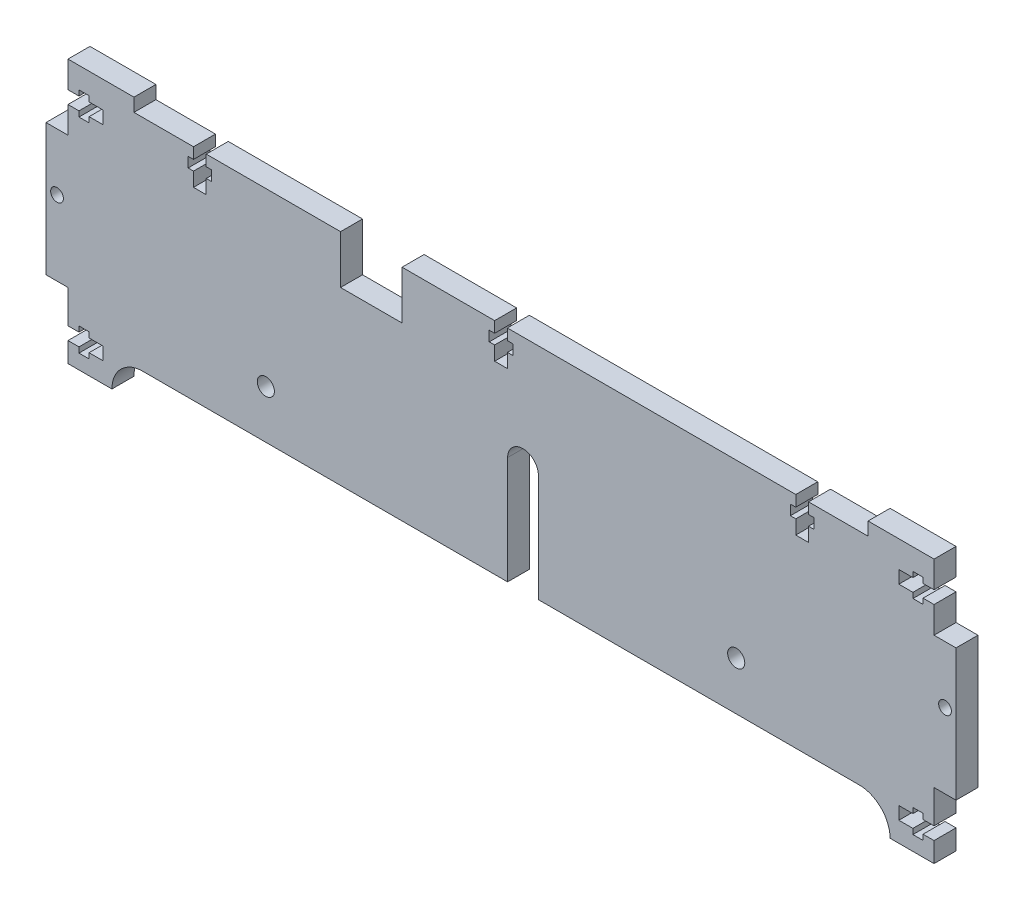
SolidWorks part; units mm, degrees
ref_plane "Front Plane" through (0, 0, 0) normal (0, 0, 1) x (1, 0, 0)
ref_plane "Top Plane" through (0, 0, 0) normal (0, 1, 0) x (1, 0, 0)
ref_plane "Right Plane" through (0, 0, 0) normal (1, 0, 0) x (0, 0, -1)
sketch "Sketch1" plane through (0, 0, 0) normal (0, 0, 1) x (1, 0, 0)
  line L18 (-83.5, 48) -> (-83.5, 51)
  line L19 (-83.5, 51) -> (-98.5, 51)
  line L20 (-98.5, 51) -> (-98.5, 44.95)
  line L21 (-98.5, 36) -> (-103.5, 36)
  line L22 (-103.5, 36) -> (-103.5, 6)
  line L23 (-103.5, 6) -> (-98.5, 6)
  line L24 (-98.5, 6) -> (-98.5, -1.55)
  line L25 (-98.5, -9) -> (-88.5, -9)
  line L26 (-81.5, -2) -> (81.5, -2)
  line L27 (88.5, -9) -> (98.5, -9)
  line L28 (98.5, -9) -> (98.5, -4.45)
  line L29 (98.5, 6) -> (103.5, 6)
  line L30 (103.5, 6) -> (103.5, 36)
  line L31 (103.5, 36) -> (98.5, 36)
  line L32 (98.5, 36) -> (98.5, 42.05)
  line L33 (98.5, 51) -> (83.5, 51)
  line L34 (83.5, 51) -> (83.5, 48)
  line L35 (83.5, 48) -> (69.95, 48)
  line L36 (-83.5, 48) -> (-83.5, 51)
  line L37 (-83.5, 51) -> (-98.5, 51)
  line L38 (-98.5, 51) -> (-98.5, 44.95)
  line L39 (-98.5, 36) -> (-103.5, 36)
  line L40 (-103.5, 36) -> (-103.5, 6)
  line L41 (-103.5, 6) -> (-98.5, 6)
  line L42 (-98.5, 6) -> (-98.5, -1.55)
  line L43 (-98.5, -9) -> (-88.5, -9)
  line L44 (-81.5, -2) -> (81.5, -2)
  line L45 (88.5, -9) -> (98.5, -9)
  line L46 (98.5, -9) -> (98.5, -4.45)
  line L47 (98.5, 6) -> (103.5, 6)
  line L48 (103.5, 6) -> (103.5, 36)
  line L49 (103.5, 36) -> (98.5, 36)
  line L50 (98.5, 36) -> (98.5, 42.05)
  line L51 (98.5, 51) -> (83.5, 51)
  line L52 (83.5, 51) -> (83.5, 48)
  line L53 (83.5, 48) -> (69.95, 48)
  line L280 (96, 46.175) -> (96, 44.95)
  line L281 (96, 46.175) -> (96, 44.95)
  line L282 (96, 44.95) -> (98.5, 44.95)
  line L283 (96, 44.95) -> (98.5, 44.95)
  line L284 (98.5, 44.95) -> (98.5, 51)
  line L285 (98.5, 44.95) -> (98.5, 51)
  line L286 (69.95, 48) -> (69.95, 45.5)
  line L287 (69.95, 48) -> (69.95, 45.5)
  line L288 (69.95, 45.5) -> (71.175, 45.5)
  line L289 (69.95, 45.5) -> (71.175, 45.5)
  line L290 (71.175, 45.5) -> (71.175, 43.2)
  line L291 (71.175, 45.5) -> (71.175, 43.2)
  line L292 (71.175, 43.2) -> (69.95, 43.2)
  line L293 (71.175, 43.2) -> (69.95, 43.2)
  line L294 (69.95, 43.2) -> (69.95, 40)
  line L295 (69.95, 43.2) -> (69.95, 40)
  line L296 (69.95, 40) -> (67.05, 40)
  line L297 (69.95, 40) -> (67.05, 40)
  line L298 (67.05, 40) -> (67.05, 43.2)
  line L299 (67.05, 40) -> (67.05, 43.2)
  line L300 (67.05, 43.2) -> (65.825, 43.2)
  line L301 (67.05, 43.2) -> (65.825, 43.2)
  line L302 (65.825, 43.2) -> (65.825, 45.5)
  line L303 (65.825, 43.2) -> (65.825, 45.5)
  line L304 (65.825, 45.5) -> (67.05, 45.5)
  line L305 (65.825, 45.5) -> (67.05, 45.5)
  line L306 (67.05, 45.5) -> (67.05, 48)
  line L307 (67.05, 45.5) -> (67.05, 48)
  line L308 (67.05, 48) -> (1.45, 48)
  line L309 (67.05, 48) -> (1.45, 48)
  line L310 (1.45, 48) -> (1.45, 45.5)
  line L311 (1.45, 48) -> (1.45, 45.5)
  line L312 (1.45, 45.5) -> (2.675, 45.5)
  line L313 (1.45, 45.5) -> (2.675, 45.5)
  line L314 (2.675, 45.5) -> (2.675, 43.2)
  line L315 (2.675, 45.5) -> (2.675, 43.2)
  line L316 (2.675, 43.2) -> (1.45, 43.2)
  line L317 (2.675, 43.2) -> (1.45, 43.2)
  line L318 (1.45, 43.2) -> (1.45, 40)
  line L319 (1.45, 43.2) -> (1.45, 40)
  line L320 (1.45, 40) -> (-1.45, 40)
  line L321 (1.45, 40) -> (-1.45, 40)
  line L322 (-1.45, 40) -> (-1.45, 43.2)
  line L323 (-1.45, 40) -> (-1.45, 43.2)
  line L324 (-1.45, 43.2) -> (-2.675, 43.2)
  line L325 (-1.45, 43.2) -> (-2.675, 43.2)
  line L326 (-2.675, 43.2) -> (-2.675, 45.5)
  line L327 (-2.675, 43.2) -> (-2.675, 45.5)
  line L328 (-2.675, 45.5) -> (-1.45, 45.5)
  line L329 (-2.675, 45.5) -> (-1.45, 45.5)
  line L330 (-1.45, 45.5) -> (-1.45, 48)
  line L331 (-1.45, 45.5) -> (-1.45, 48)
  line L332 (-1.45, 48) -> (-67.05, 48)
  line L333 (-1.45, 48) -> (-67.05, 48)
  line L334 (-67.05, 48) -> (-67.05, 45.5)
  line L335 (-67.05, 48) -> (-67.05, 45.5)
  line L336 (-67.05, 45.5) -> (-65.825, 45.5)
  line L337 (-67.05, 45.5) -> (-65.825, 45.5)
  line L338 (-65.825, 45.5) -> (-65.825, 43.2)
  line L339 (-65.825, 45.5) -> (-65.825, 43.2)
  line L340 (-65.825, 43.2) -> (-67.05, 43.2)
  line L341 (-65.825, 43.2) -> (-67.05, 43.2)
  line L342 (-67.05, 43.2) -> (-67.05, 40)
  line L343 (-67.05, 43.2) -> (-67.05, 40)
  line L344 (-67.05, 40) -> (-69.95, 40)
  line L345 (-67.05, 40) -> (-69.95, 40)
  line L346 (-69.95, 40) -> (-69.95, 43.2)
  line L347 (-69.95, 40) -> (-69.95, 43.2)
  line L348 (-69.95, 43.2) -> (-71.175, 43.2)
  line L349 (-69.95, 43.2) -> (-71.175, 43.2)
  line L350 (-71.175, 43.2) -> (-71.175, 45.5)
  line L351 (-71.175, 43.2) -> (-71.175, 45.5)
  line L352 (-71.175, 45.5) -> (-69.95, 45.5)
  line L353 (-71.175, 45.5) -> (-69.95, 45.5)
  line L354 (-69.95, 45.5) -> (-69.95, 48)
  line L355 (-69.95, 45.5) -> (-69.95, 48)
  line L356 (-69.95, 48) -> (-83.5, 48)
  line L357 (-69.95, 48) -> (-83.5, 48)
  line L358 (-98.5, 44.95) -> (-96, 44.95)
  line L359 (-98.5, 44.95) -> (-96, 44.95)
  line L360 (-96, 44.95) -> (-96, 46.175)
  line L361 (-96, 44.95) -> (-96, 46.175)
  line L362 (-96, 46.175) -> (-93.7, 46.175)
  line L363 (-96, 46.175) -> (-93.7, 46.175)
  line L364 (-93.7, 46.175) -> (-93.7, 44.95)
  line L365 (-93.7, 46.175) -> (-93.7, 44.95)
  line L366 (-93.7, 44.95) -> (-90.5, 44.95)
  line L367 (-93.7, 44.95) -> (-90.5, 44.95)
  line L368 (-90.5, 44.95) -> (-90.5, 42.05)
  line L369 (-90.5, 44.95) -> (-90.5, 42.05)
  line L370 (-90.5, 42.05) -> (-93.7, 42.05)
  line L371 (-90.5, 42.05) -> (-93.7, 42.05)
  line L372 (-93.7, 42.05) -> (-93.7, 40.825)
  line L373 (-93.7, 42.05) -> (-93.7, 40.825)
  line L374 (-93.7, 40.825) -> (-96, 40.825)
  line L375 (-93.7, 40.825) -> (-96, 40.825)
  line L376 (-96, 40.825) -> (-96, 42.05)
  line L377 (-96, 40.825) -> (-96, 42.05)
  line L378 (-96, 42.05) -> (-98.5, 42.05)
  line L379 (-96, 42.05) -> (-98.5, 42.05)
  line L380 (-98.5, 42.05) -> (-98.5, 36)
  line L381 (-98.5, 42.05) -> (-98.5, 36)
  line L382 (-98.5, -1.55) -> (-96, -1.55)
  line L383 (-98.5, -1.55) -> (-96, -1.55)
  line L384 (-96, -1.55) -> (-96, -0.325)
  line L385 (-96, -1.55) -> (-96, -0.325)
  line L386 (-96, -0.325) -> (-93.7, -0.325)
  line L387 (-96, -0.325) -> (-93.7, -0.325)
  line L388 (-93.7, -0.325) -> (-93.7, -1.55)
  line L389 (-93.7, -0.325) -> (-93.7, -1.55)
  line L390 (-93.7, -1.55) -> (-90.5, -1.55)
  line L391 (-93.7, -1.55) -> (-90.5, -1.55)
  line L392 (-90.5, -1.55) -> (-90.5, -4.45)
  line L393 (-90.5, -1.55) -> (-90.5, -4.45)
  line L394 (-90.5, -4.45) -> (-93.7, -4.45)
  line L395 (-90.5, -4.45) -> (-93.7, -4.45)
  line L396 (-93.7, -4.45) -> (-93.7, -5.675)
  line L397 (-93.7, -4.45) -> (-93.7, -5.675)
  line L398 (-93.7, -5.675) -> (-96, -5.675)
  line L399 (-93.7, -5.675) -> (-96, -5.675)
  line L400 (-96, -5.675) -> (-96, -4.45)
  line L401 (-96, -5.675) -> (-96, -4.45)
  line L402 (-96, -4.45) -> (-98.5, -4.45)
  line L403 (-96, -4.45) -> (-98.5, -4.45)
  line L404 (-98.5, -4.45) -> (-98.5, -9)
  line L405 (-98.5, -4.45) -> (-98.5, -9)
  line L406 (98.5, -4.45) -> (96, -4.45)
  line L407 (98.5, -4.45) -> (96, -4.45)
  line L408 (96, -4.45) -> (96, -5.675)
  line L409 (96, -4.45) -> (96, -5.675)
  line L410 (96, -5.675) -> (93.7, -5.675)
  line L411 (96, -5.675) -> (93.7, -5.675)
  line L412 (93.7, -5.675) -> (93.7, -4.45)
  line L413 (93.7, -5.675) -> (93.7, -4.45)
  line L414 (93.7, -4.45) -> (90.5, -4.45)
  line L415 (93.7, -4.45) -> (90.5, -4.45)
  line L416 (90.5, -4.45) -> (90.5, -1.55)
  line L417 (90.5, -4.45) -> (90.5, -1.55)
  line L418 (90.5, -1.55) -> (93.7, -1.55)
  line L419 (90.5, -1.55) -> (93.7, -1.55)
  line L420 (93.7, -1.55) -> (93.7, -0.325)
  line L421 (93.7, -1.55) -> (93.7, -0.325)
  line L422 (93.7, -0.325) -> (96, -0.325)
  line L423 (93.7, -0.325) -> (96, -0.325)
  line L424 (96, -0.325) -> (96, -1.55)
  line L425 (96, -0.325) -> (96, -1.55)
  line L426 (96, -1.55) -> (98.5, -1.55)
  line L427 (96, -1.55) -> (98.5, -1.55)
  line L428 (98.5, -1.55) -> (98.5, 6)
  line L429 (98.5, -1.55) -> (98.5, 6)
  line L430 (98.5, 42.05) -> (96, 42.05)
  line L431 (98.5, 42.05) -> (96, 42.05)
  line L432 (96, 42.05) -> (96, 40.825)
  line L433 (96, 42.05) -> (96, 40.825)
  line L434 (96, 40.825) -> (93.7, 40.825)
  line L435 (96, 40.825) -> (93.7, 40.825)
  line L436 (93.7, 40.825) -> (93.7, 42.05)
  line L437 (93.7, 40.825) -> (93.7, 42.05)
  line L438 (93.7, 42.05) -> (90.5, 42.05)
  line L439 (93.7, 42.05) -> (90.5, 42.05)
  line L440 (90.5, 42.05) -> (90.5, 44.95)
  line L441 (90.5, 42.05) -> (90.5, 44.95)
  line L442 (90.5, 44.95) -> (93.7, 44.95)
  line L443 (90.5, 44.95) -> (93.7, 44.95)
  line L444 (93.7, 44.95) -> (93.7, 46.175)
  line L445 (93.7, 44.95) -> (93.7, 46.175)
  line L446 (93.7, 46.175) -> (96, 46.175)
  line L447 (93.7, 46.175) -> (96, 46.175)
  arc A2 (-81.5, -2) -> (-88.5, -9) centre (-81.5, -9) ccw
  arc A3 (88.5, -9) -> (81.5, -2) centre (81.5, -9) ccw
  arc A4 (-81.5, -2) -> (-88.5, -9) centre (-81.5, -9) ccw
  arc A5 (88.5, -9) -> (81.5, -2) centre (81.5, -9) ccw
  dimension "D1" = 0
extrude "Boss-Extrude1" add sketch "Sketch1" along normal blind 5
sketch "Sketch2" plane through (0, 0, 5) normal (0, 0, 1) x (1, 0, 0)
  line L0 (-103.5, 36) -> (-103.5, 6) construction
  line L1 (-36.5, 49) -> (-22.5, 49)
  line L2 (-36.5, 49) -> (-36.5, 37)
  line L3 (-36.5, 37) -> (-22.5, 37)
  line L4 (-22.5, 49) -> (-22.5, 37)
  line L5 (-98.5, -9) -> (-88.5, -9) construction
  dimension "D1" = 81
  dimension "D2" = 14
  dimension "D3" = 12
  dimension "D4" = 46
extrude "Cut-Extrude1" cut sketch "Sketch2" against normal through all
sketch "Sketch3" plane through (0, 0, 5) normal (0, 0, 1) x (1, 0, 0)
  line L0 (-103.5, 36) -> (-103.5, 6) construction
  line L1 (1.5, -2) -> (8.5, -2)
  line L2 (1.5, -2) -> (1.5, 22.5)
  line L3 (1.5, 22.5) -> (8.5, 22.5)
  line L4 (8.5, -2) -> (8.5, 22.5)
  line L6 (5, 22.5) -> (5, -2) construction
  line L9 (88.5, -9) -> (98.5, -9) construction
  line L10 (-81.5, -2) -> (81.5, -2) construction
  circle A0 centre (5, 22.5) radius 3.5
  point P4 (29.5778, -2)
  point P14 (0, 0)
  point P15 (0, 0)
  dimension "D1" = 7
  dimension "D2" = 35
  dimension "D3" = 105
extrude "Cut-Extrude2" cut sketch "Sketch3" against normal through all contours L4 L3 L2 L1 | A0
sketch "Sketch4" plane through (0, 0, 5) normal (0, 0, 1) x (1, 0, 0)
  line L0 (-67.05, 51) -> (-69.95, 51) construction
  line L1 (1.45, 51) -> (-1.45, 51) construction
  line L2 (1.45, 48) -> (1.45, 51) construction
  line L3 (-1.45, 51) -> (-1.45, 48) construction
  line L4 (-69.95, 51) -> (-69.95, 48) construction
  line L5 (-67.05, 48) -> (-67.05, 51) construction
  line L6 (-67.05, 51) -> (-69.95, 51) construction
  line L7 (1.45, 51) -> (-1.45, 51) construction
  line L8 (1.45, 48) -> (1.45, 51) construction
  line L9 (-1.45, 51) -> (-1.45, 48) construction
  line L10 (-69.95, 51) -> (-69.95, 48) construction
  line L11 (-67.05, 48) -> (-67.05, 51) construction
  line L12 (-103.5, 21.55) -> (-103.5, 24.45) construction
  line L13 (-103.5, 21.55) -> (-103.5, 24.45) construction
  line L14 (-103.5, 44.95) -> (-103.5, 42.05) construction
  line L15 (-103.5, -1.55) -> (-103.5, -4.45) construction
  line L16 (-103.5, 44.95) -> (-103.5, 42.05) construction
  line L17 (-103.5, -1.55) -> (-103.5, -4.45) construction
  line L18 (-103.5, 23) -> (-83.698, 23) construction
  line L19 (-101, 36) -> (-101, 23) construction
  line L20 (-103.5, 36) -> (-98.5, 36) construction
  line L21 (-103.5, 43.5) -> (-94.9093, 43.5) construction
  line L22 (-98.5, 51) -> (-98.5, 44.95) construction
  line L23 (-98.5, 44.95) -> (-90.5, 44.95)
  line L24 (-98.5, 44.95) -> (-98.5, 42.05)
  line L25 (-98.5, 42.05) -> (-90.5, 42.05)
  line L26 (-90.5, 44.95) -> (-90.5, 42.05)
  line L27 (-96, 46.175) -> (-93.7, 46.175)
  line L28 (-96, 46.175) -> (-96, 40.825)
  line L29 (-96, 40.825) -> (-93.7, 40.825)
  line L30 (-93.7, 46.175) -> (-93.7, 40.825)
  line L31 (-103.5, 20.325) -> (-69.95, 20.325) construction
  line L32 (-98.5, -9) -> (-98.5, 6) construction
  line L33 (-98.5, -1.55) -> (-90.5, -1.55)
  line L34 (-98.5, -1.55) -> (-98.5, -4.45)
  line L35 (-98.5, -4.45) -> (-90.5, -4.45)
  line L36 (-90.5, -1.55) -> (-90.5, -4.45)
  line L37 (-103.5, -4.45) -> (-98.5, -4.45) construction
  line L38 (-90.5, 42.05) -> (-90.5, -1.55) construction
  line L39 (-96, -0.325) -> (-96, 40.825) construction
  line L40 (-96, -0.325) -> (-93.7, -0.325)
  line L41 (-96, -0.325) -> (-96, -5.675)
  line L42 (-96, -5.675) -> (-93.7, -5.675)
  line L43 (-93.7, -0.325) -> (-93.7, -5.675)
  line L44 (-93.7, 40.825) -> (-93.7, -0.325) construction
  line L45 (-96, -3) -> (-98.5, -3) construction
  line L46 (0, 0) -> (0, -28.1193) construction
  line L47 (96, -3) -> (98.5, -3) construction
  line L48 (93.7, 40.825) -> (93.7, -0.325) construction
  line L49 (96, -0.325) -> (96, 40.825) construction
  line L50 (90.5, 42.05) -> (90.5, -1.55) construction
  line L51 (103.5, 43.5) -> (94.9093, 43.5) construction
  line L52 (101, 36) -> (101, 23) construction
  line L53 (103.5, 23) -> (83.698, 23) construction
  line L54 (103.5, -1.55) -> (103.5, -4.45) construction
  line L55 (103.5, 44.95) -> (103.5, 42.05) construction
  line L56 (103.5, 21.55) -> (103.5, 24.45) construction
  line L57 (93.7, -0.325) -> (93.7, -5.675)
  line L58 (96, -5.675) -> (93.7, -5.675)
  line L59 (96, -0.325) -> (96, -5.675)
  line L60 (96, -0.325) -> (93.7, -0.325)
  line L61 (90.5, -1.55) -> (90.5, -4.45)
  line L62 (98.5, -4.45) -> (90.5, -4.45)
  line L63 (98.5, -1.55) -> (98.5, -4.45)
  line L64 (98.5, -1.55) -> (90.5, -1.55)
  line L65 (93.7, 46.175) -> (93.7, 40.825)
  line L66 (96, 40.825) -> (93.7, 40.825)
  line L67 (96, 46.175) -> (96, 40.825)
  line L68 (96, 46.175) -> (93.7, 46.175)
  line L69 (90.5, 44.95) -> (90.5, 42.05)
  line L70 (98.5, 42.05) -> (90.5, 42.05)
  line L71 (98.5, 44.95) -> (98.5, 42.05)
  line L72 (98.5, 44.95) -> (90.5, 44.95)
  line L73 (51, 48) -> (-83.5, 48) construction
  line L74 (-69.95, 48) -> (-67.05, 48)
  line L75 (-69.95, 48) -> (-69.95, 40)
  line L76 (-69.95, 40) -> (-67.05, 40)
  line L77 (-67.05, 48) -> (-67.05, 40)
  line L78 (-71.175, 45.5) -> (-65.825, 45.5)
  line L79 (-71.175, 45.5) -> (-71.175, 43.2)
  line L80 (-71.175, 43.2) -> (-65.825, 43.2)
  line L81 (-65.825, 45.5) -> (-65.825, 43.2)
  line L82 (-68.5, 45.5) -> (-68.5, 48) construction
  line L83 (-67.05, 40) -> (-1.45, 40) construction
  line L84 (-1.45, 48) -> (1.45, 48)
  line L85 (-1.45, 48) -> (-1.45, 40)
  line L86 (-1.45, 40) -> (1.45, 40)
  line L87 (1.45, 48) -> (1.45, 40)
  line L88 (-65.825, 45.5) -> (-2.675, 45.5) construction
  line L89 (-2.675, 45.5) -> (2.675, 45.5)
  line L90 (-2.675, 45.5) -> (-2.675, 43.2)
  line L91 (-2.675, 43.2) -> (2.675, 43.2)
  line L92 (2.675, 45.5) -> (2.675, 43.2)
  line L93 (-65.825, 43.2) -> (-2.675, 43.2) construction
  line L94 (0, 45.5) -> (0, 48) construction
  line L95 (68.5, 45.5) -> (68.5, 48) construction
  line L96 (67.05, 48) -> (67.05, 51) construction
  line L97 (69.95, 51) -> (69.95, 48) construction
  line L98 (67.05, 51) -> (69.95, 51) construction
  line L99 (65.825, 45.5) -> (65.825, 43.2)
  line L100 (71.175, 43.2) -> (65.825, 43.2)
  line L101 (71.175, 45.5) -> (71.175, 43.2)
  line L102 (71.175, 45.5) -> (65.825, 45.5)
  line L103 (67.05, 48) -> (67.05, 40)
  line L104 (69.95, 40) -> (67.05, 40)
  line L105 (69.95, 48) -> (69.95, 40)
  line L106 (69.95, 48) -> (67.05, 48)
  circle A0 centre (-101, 23) radius 1.45
  circle A1 centre (101, 23) radius 1.45
  point P36 (-96, 43.5)
  point P121 (0, 0)
  point P122 (0, 0)
  point P123 (-98.5, -1.5)
  point P124 (0, 0)
  point P125 (-98.5, -2)
  point P127 (0, 0)
  point P128 (-98.5, -1.55)
  dimension "D1" = 2.9
  dimension "D2" = 8
  dimension "D3" = 2.3
  dimension "D4" = 2.5
  dimension "D5" = 5.35
  dimension "D6" = 8
  dimension "D7" = 2.5
extrude "Cut-Extrude3" cut sketch "Sketch4" against normal through all contours L35 L36 L33 L34 | L42 L43 L40 L41 | L25 L26 L23 L24 | L27 L30 L29 L28 | L76 L77 L74 L75 | L79 L80 L81 L78 | A0 | L86 L87 L84 L85 | L91 L92 L89 L90 | L104 L103 L106 L105 | L100 L99 L102 L101 | L70 L69 L72 L71 | L66 L65 L68 L67 | L62 L61 L64 L63 | L58 L57 L60 L59 | A1
sketch "Sketch5" plane through (0, 0, 5) normal (0, 0, 1) x (1, 0, 0)
  line L0 (-103.5, 10.95) -> (-103.5, 7.05) construction
  line L1 (-103.5, 10.95) -> (-103.5, 7.05) construction
  line L2 (-103.5, 9) -> (114.2132, 9) construction
  line L3 (-103.5, 10.95) -> (-43.5188, 10.95) construction
  line L4 (-103.5, 36) -> (-103.5, 6) construction
  line L5 (103.5, 6) -> (103.5, 36) construction
  circle A0 centre (-53.5, 9) radius 1.95
  circle A1 centre (53.5, 9) radius 1.95
  dimension "D1" = 3.9
  dimension "D2" = 50
  dimension "D3" = 50
extrude "Cut-Extrude4" cut sketch "Sketch5" against normal through all
